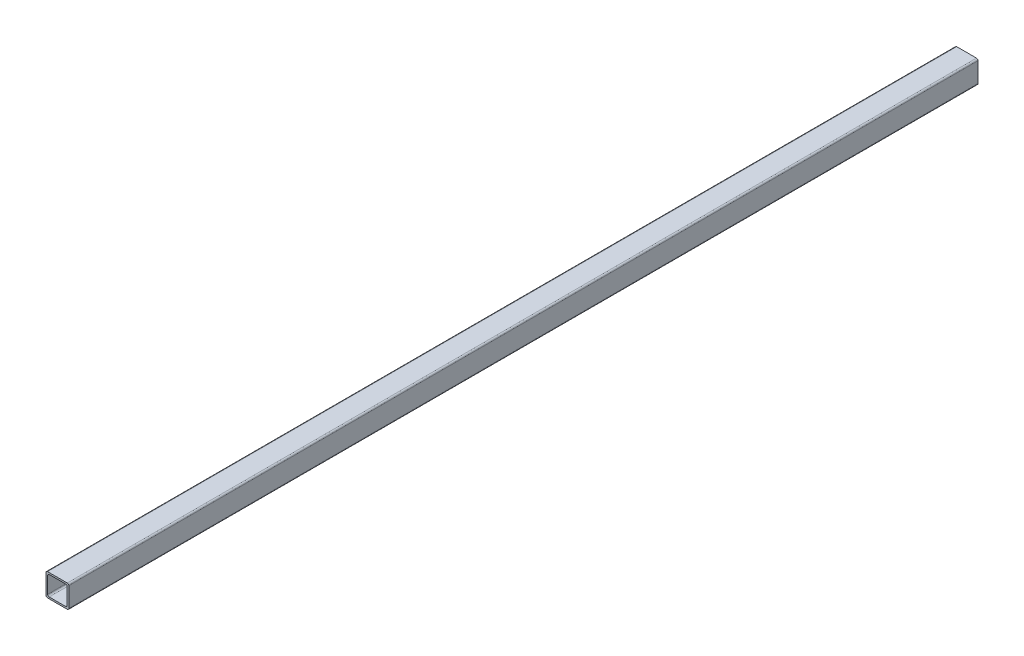
SolidWorks part; units mm, degrees
material "ASTM A500 Grade B Steel"
ref_plane "Front Plane" through (0, 0, 0) normal (0, 0, 1) x (1, 0, 0)
ref_plane "Top Plane" through (0, 0, 0) normal (0, 1, 0) x (1, 0, 0)
ref_plane "Right Plane" through (0, 0, 0) normal (1, 0, 0) x (0, 0, -1)
sketch "Sketch1" plane through (0, 0, 0) normal (0, 0, 1) x (1, 0, 0)
  line L0 (5.3086, -2.7686) -> (32.7914, -2.7686)
  line L1 (2.54, 0) -> (35.56, 0)
  line L2 (0, -2.54) -> (0, -35.56)
  line L3 (2.54, -38.1) -> (35.56, -38.1)
  line L4 (38.1, -2.54) -> (38.1, -35.56)
  line L5 (35.3314, -5.3086) -> (35.3314, -32.7914)
  line L6 (5.3086, -35.3314) -> (32.7914, -35.3314)
  line L7 (2.7686, -5.3086) -> (2.7686, -32.7914)
  line L8 (0, 0) -> (0, -38.1) construction
  line L9 (0, -38.1) -> (38.1, -38.1) construction
  line L10 (38.1, 0) -> (38.1, -38.1) construction
  line L11 (2.7686, -2.7686) -> (2.7686, -35.3314) construction
  line L12 (2.7686, -35.3314) -> (35.3314, -35.3314) construction
  line L13 (35.3314, -2.7686) -> (35.3314, -35.3314) construction
  line L14 (2.7686, -2.7686) -> (35.3314, -2.7686) construction
  line L15 (0, 0) -> (38.1, 0) construction
  arc A0 (0, -35.56) -> (2.54, -38.1) centre (2.54, -35.56) ccw
  arc A1 (38.1, -35.56) -> (35.56, -38.1) centre (35.56, -35.56) cw
  arc A2 (2.7686, -32.7914) -> (5.3086, -35.3314) centre (5.3086, -32.7914) ccw
  arc A3 (32.7914, -35.3314) -> (35.3314, -32.7914) centre (32.7914, -32.7914) ccw
  arc A4 (35.3314, -5.3086) -> (32.7914, -2.7686) centre (32.7914, -5.3086) ccw
  arc A5 (38.1, -2.54) -> (35.56, 0) centre (35.56, -2.54) ccw
  arc A6 (0, -2.54) -> (2.54, 0) centre (2.54, -2.54) cw
  arc A7 (5.3086, -2.7686) -> (2.7686, -5.3086) centre (5.3086, -5.3086) ccw
  point P12 (0, -38.1)
  dimension "D4" = 2.54
  dimension "D3" = 2.7686
extrude "Boss-Extrude1" add sketch "Sketch1" along normal blind 1520
